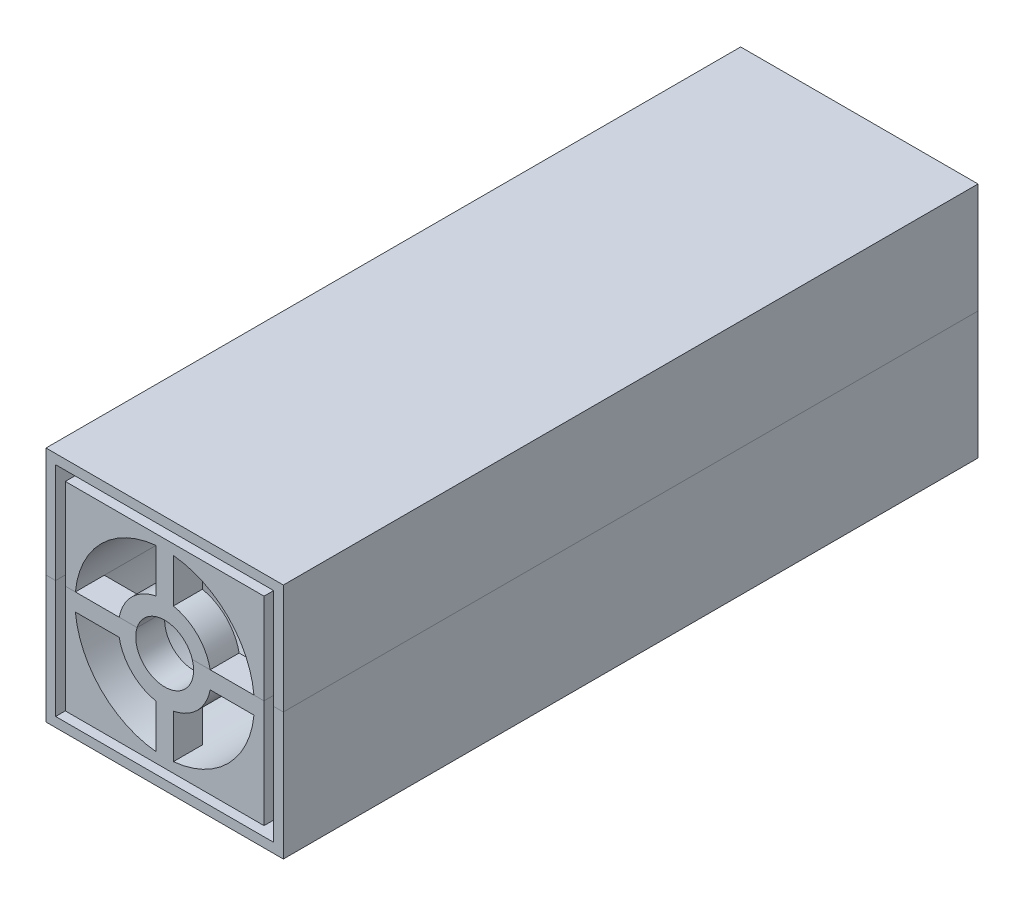
SolidWorks part; units mm, degrees
ref_plane "Front Plane" through (0, 0, 0) normal (0, 0, 1) x (1, 0, 0)
ref_plane "Top Plane" through (0, 0, 0) normal (0, 1, 0) x (1, 0, 0)
ref_plane "Right Plane" through (0, 0, 0) normal (1, 0, 0) x (0, 0, -1)
sketch "Sketch2" plane through (0, 0, 0) normal (0, 0, 1) x (1, 0, 0)
  line L1 (26.035, -26.035) -> (-26.035, -26.035)
  line L2 (26.035, -26.035) -> (26.035, 26.035)
  line L3 (26.035, 26.035) -> (-26.035, 26.035)
  line L4 (-26.035, -26.035) -> (-26.035, 26.035)
  line L5 (26.035, -26.035) -> (-26.035, 26.035) construction
  line L6 (26.035, 26.035) -> (-26.035, -26.035) construction
  dimension "D1" = 52.07
  dimension "D2" = 52.07
extrude "Boss-Extrude1" add sketch "Sketch2" against normal blind 152.4
sketch "Sketch3" plane through (0, 0, 0) normal (0, 0, 1) x (1, 0, 0)
  line L0 (-26.035, 26.035) -> (-26.035, -26.035) construction
  line L1 (23.9183, -23.9183) -> (-23.9183, -23.9183)
  line L2 (23.9183, -23.9183) -> (23.9183, 23.9183)
  line L3 (23.9183, 23.9183) -> (-23.9183, 23.9183)
  line L4 (-23.9183, -23.9183) -> (-23.9183, 23.9183)
  line L5 (23.9183, -23.9183) -> (-23.9183, 23.9183) construction
  line L6 (23.9183, 23.9183) -> (-23.9183, -23.9183) construction
  line L7 (-26.035, -26.035) -> (26.035, -26.035) construction
  line L8 (26.035, 26.035) -> (-26.035, 26.035) construction
  line L9 (26.035, -26.035) -> (26.035, 26.035) construction
  line L11 (21.8018, -21.8018) -> (-21.8018, -21.8018)
  line L12 (21.8018, -21.8018) -> (21.8018, 21.8018)
  line L13 (21.8018, 21.8018) -> (-21.8018, 21.8018)
  line L14 (-21.8018, -21.8018) -> (-21.8018, 21.8018)
  line L15 (21.8018, -21.8018) -> (-21.8018, 21.8018) construction
  line L16 (21.8018, 21.8018) -> (-21.8018, -21.8018) construction
  point P0 (0, 0)
  point P14 (0, 0)
  dimension "D1" = 2.1167
  dimension "D2" = 2.1167
  dimension "D3" = 2.1167
  dimension "D4" = 2.1167
  dimension "D5" = 2.1166
  dimension "D6" = 2.1166
  dimension "D7" = 2.1166
extrude "Cut-Extrude1" cut sketch "Sketch3" against normal blind 12.7 contours L4 L1 L2 L3 L11 L14 L13 L12
sketch "Sketch4" plane through (0, 0, 0) normal (0, 0, 1) x (1, 0, 0)
  circle A0 centre (0, 0) radius 19.685
extrude "Cut-Extrude2" cut sketch "Sketch4" against normal blind 146.05
sketch "Sketch5" plane through (0, 0, 0) normal (0, 0, 1) x (1, 0, 0)
  line L0 (21.8018, 21.8018) -> (-21.8018, 21.8018) construction
  line L1 (-1.905, 21.8018) -> (1.905, 21.8018)
  line L2 (-1.905, 21.8018) -> (-1.905, -21.8018)
  line L3 (-1.905, -21.8018) -> (1.905, -21.8018)
  line L4 (1.905, 21.8018) -> (1.905, -21.8018)
  line L5 (21.8018, -21.8018) -> (-21.8018, -21.8018) construction
  line L6 (-26.035, -26.035) -> (26.035, -26.035) construction
  line L7 (-26.035, 26.035) -> (-26.035, -26.035) construction
  line L8 (26.035, -26.035) -> (26.035, 26.035) construction
  line L9 (-21.8018, -21.8018) -> (-21.8018, 21.8018) construction
  line L10 (21.8018, -1.905) -> (-21.8018, -1.905)
  line L11 (21.8018, -1.905) -> (21.8018, 1.905)
  line L12 (21.8018, 1.905) -> (-21.8018, 1.905)
  line L13 (-21.8018, -1.905) -> (-21.8018, 1.905)
  line L14 (21.8018, -1.905) -> (-21.8018, 1.905) construction
  line L15 (21.8018, 1.905) -> (-21.8018, -1.905) construction
  circle A0 centre (0, 0) radius 10.16
  point P12 (0, 0)
  dimension "D1" = 43.6035
  dimension "D2" = 24.13
  dimension "D3" = 24.13
  dimension "D4" = 24.13
extrude "Boss-Extrude2" add sketch "Sketch5" against normal blind 6.35
sketch "Sketch6" plane through (0, 0, 0) normal (0, 0, 1) x (1, 0, 0)
  circle A0 centre (0, 0) radius 6.35
extrude "Cut-Extrude3" cut sketch "Sketch6" against normal through all
sketch "Sketch7" plane through (0, -26.035, 0) normal (0, -1, 0) x (1, 0, 0)
  line L0 (26.035, -152.4) -> (26.035, 0) construction
  line L1 (19.685, -120.65) -> (-19.685, -120.65)
  line L2 (19.685, -120.65) -> (19.685, -146.05)
  line L3 (19.685, -146.05) -> (-19.685, -146.05)
  line L4 (-19.685, -120.65) -> (-19.685, -146.05)
  line L5 (-26.035, -152.4) -> (26.035, -152.4) construction
  line L6 (-26.035, -152.4) -> (-26.035, 0) construction
  dimension "D1" = 6.35
  dimension "D2" = 6.35
  dimension "D3" = 6.35
  dimension "D4" = 25.4
extrude "Cut-Extrude4" cut sketch "Sketch7" against normal blind 26.035
ref_plane "Plane1" through (0, 1.905, 0) normal (0, 1, 0) x (1, 0, 0)
split "Split1" trim tools "Plane1" bodies to split 106 resulting bodies 107 108
